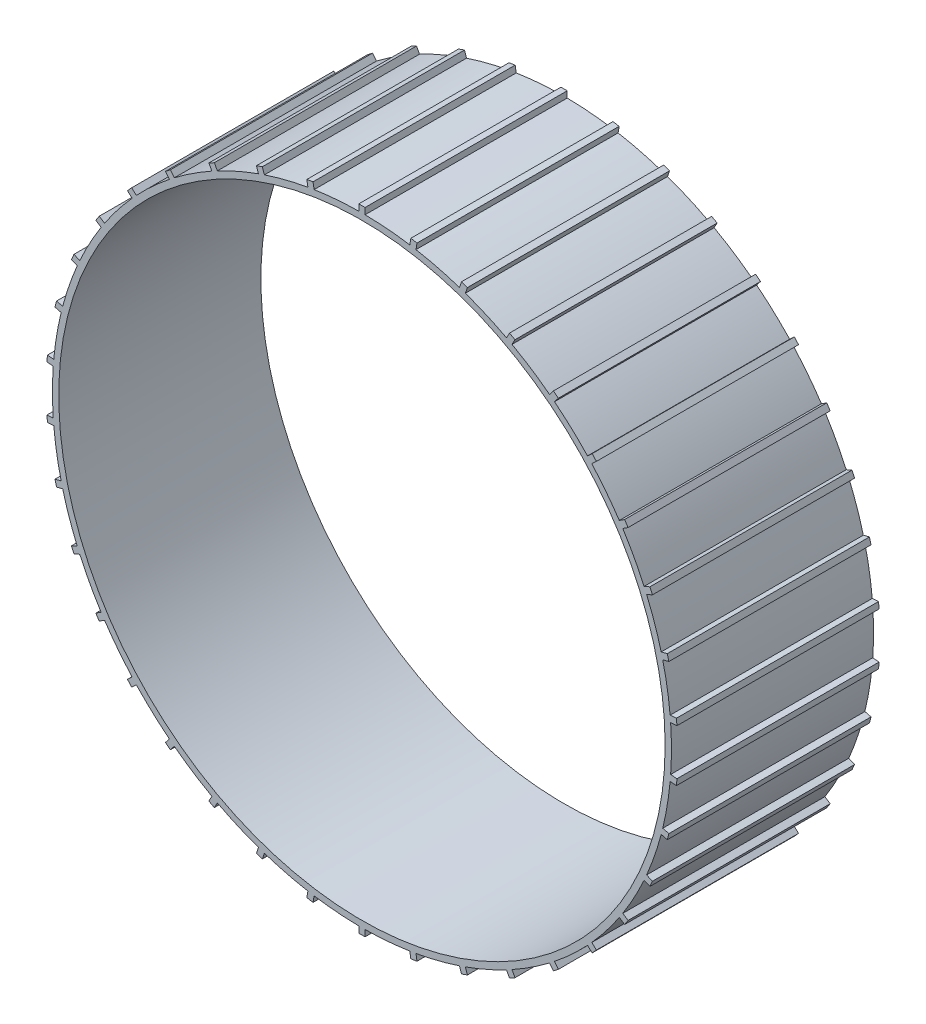
SolidWorks part; units mm, degrees
material "Rubber"
ref_plane "Front Plane" through (0, 0, 0) normal (0, 0, 1) x (1, 0, 0)
ref_plane "Top Plane" through (0, 0, 0) normal (0, 1, 0) x (1, 0, 0)
ref_plane "Right Plane" through (0, 0, 0) normal (1, 0, 0) x (0, 0, -1)
sketch "Sketch1" plane through (0, 0, 0) normal (0, 0, 1) x (1, 0, 0)
  circle A0 centre (0, 0) radius 155.575
  circle A1 centre (0, 0) radius 152.4
  dimension "D1" = 304.8
  dimension "D2" = 311.15
extrude "Boss-Extrude1" add sketch "Sketch1" along normal blind 101.6
sketch "Sketch2" plane through (0, 0, 101.6) normal (0, 0, 1) x (1, 0, 0)
  line L0 (-1.5748, 155.567) -> (-1.5748, 158.75)
  line L1 (-1.5748, 158.75) -> (1.5748, 158.75)
  line L2 (1.5748, 158.75) -> (1.5748, 155.567)
  circle A0 centre (0, 0) radius 155.575 construction
  circle A2 centre (0, 0) radius 155.575
  arc A3 (-1.5748, 155.567) -> (1.5748, 155.567) centre (0, 0) ccw
  circle M1 centre (0, 0) radius 155.575
  dimension "D1" = 1.5748
  dimension "D2" = 1.5748
  dimension "D3" = 158.75
  dimension "D4" = 0
extrude "Boss-Extrude2" add sketch "Sketch2" against normal through all contours L2 L1 L0 M1
pattern_circular "CirPattern1" count 38 over 360 about axis through (0, 0, 0) along (0, 0, 1) of "Boss-Extrude2"
